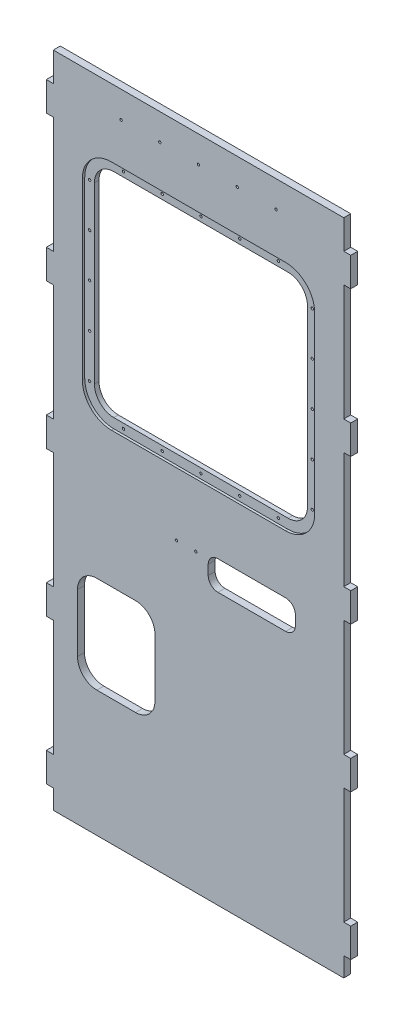
SolidWorks part; units mm, degrees
ref_plane "Front" through (0, 0, 0) normal (0, 0, 1) x (1, 0, 0)
ref_plane "Top" through (0, 0, 0) normal (0, 1, 0) x (1, 0, 0)
ref_plane "Right" through (0, 0, 0) normal (1, 0, 0) x (0, 0, -1)
sketch "Sketch2" plane through (0, 0, 0) normal (0, 0, 1) x (1, 0, 0)
  line L1 (0, 0) -> (381, 0)
  line L2 (0, 0) -> (0, 1727.2)
  line L3 (0, 1727.2) -> (381, 1727.2)
  line L4 (381, 0) -> (381, 1727.2)
  dimension "D1" = 381
  dimension "D2" = 1727.2
extrude "Boss-Extrude1" add sketch "Sketch2" against normal blind 18.288
sketch "Sketch3" plane through (0, 0, 0) normal (0, 0, 1) x (1, 0, 0)
  line L0 (0, 1727.2) -> (0, 0) construction
  line L1 (0, 50.8) -> (-18.288, 50.8)
  line L2 (0, 50.8) -> (0, 127)
  line L3 (0, 127) -> (-18.288, 127)
  line L4 (-18.288, 50.8) -> (-18.288, 127)
  dimension "D1" = 18.288
  dimension "D2" = 76.2
  dimension "D3" = 50.8
extrude "Boss-Extrude2" add sketch "Sketch3" against normal blind 18.288
pattern_linear "LPattern1" count 5 spacing 381 along (0, 1, 0) of "Boss-Extrude2"
mirror "Mirror1" about plane through (381, 0, -18.288) normal (1, 0, 0) of "Boss-Extrude1", "LPattern1", "Boss-Extrude2"
sketch "Sketch4" plane through (0, 0, 0) normal (0, 0, 1) x (1, 0, 0)
  line L0 (101.6, 1524) -> (660.4, 965.2) construction
  line L1 (152.4, 1524) -> (609.6, 1524)
  line L2 (101.6, 1473.2) -> (101.6, 1016)
  line L3 (152.4, 965.2) -> (609.6, 965.2)
  line L4 (660.4, 1473.2) -> (660.4, 1016)
  line L5 (660.4, 1524) -> (101.6, 965.2) construction
  line L7 (762, 1727.2) -> (0, 1727.2) construction
  line L96 (762, 1193.8) -> (762, 889) construction
  arc A0 (609.6, 965.2) -> (660.4, 1016) centre (609.6, 1016) ccw
  arc A1 (101.6, 1016) -> (152.4, 965.2) centre (152.4, 1016) ccw
  arc A2 (152.4, 1524) -> (101.6, 1473.2) centre (152.4, 1473.2) ccw
  arc A3 (609.6, 1524) -> (660.4, 1473.2) centre (609.6, 1473.2) cw
  point P6 (381, 1244.6)
  dimension "D5" = 50.8
  dimension "D1" = 558.8
  dimension "D2" = 558.8
  dimension "D4" = 482.6
  dimension "D6" = 381
extrude "Cut-Extrude2" cut sketch "Sketch4" against normal through all
sketch "Sketch5" plane through (0, 0, 0) normal (0, 0, 1) x (1, 0, 0)
  line L0 (101.6, 1524) -> (660.4, 965.2) construction
  line L1 (152.4, 1524) -> (609.6, 1524)
  line L2 (101.6, 1473.2) -> (101.6, 1016)
  line L3 (152.4, 965.2) -> (609.6, 965.2)
  line L4 (660.4, 1473.2) -> (660.4, 1016)
  line L5 (660.4, 1524) -> (101.6, 965.2) construction
  line L6 (762, 1727.2) -> (0, 1727.2) construction
  line L7 (381, 1727.2) -> (381, 0) construction
  line L8 (0, 0) -> (762, 0) construction
  line L96 (152.4, 1549.4) -> (609.6, 1549.4)
  line L97 (685.8, 1473.2) -> (685.8, 1016)
  line L98 (152.4, 939.8) -> (609.6, 939.8)
  line L99 (76.2, 1473.2) -> (76.2, 1016)
  arc A0 (609.6, 965.2) -> (660.4, 1016) centre (609.6, 1016) ccw
  arc A1 (101.6, 1016) -> (152.4, 965.2) centre (152.4, 1016) ccw
  arc A2 (152.4, 1524) -> (101.6, 1473.2) centre (152.4, 1473.2) ccw
  arc A3 (609.6, 1524) -> (660.4, 1473.2) centre (609.6, 1473.2) cw
  arc A4 (609.6, 1549.4) -> (685.8, 1473.2) centre (609.6, 1473.2) cw
  arc A5 (609.6, 939.8) -> (685.8, 1016) centre (609.6, 1016) ccw
  arc A6 (76.2, 1016) -> (152.4, 939.8) centre (152.4, 1016) ccw
  arc A7 (152.4, 1549.4) -> (76.2, 1473.2) centre (152.4, 1473.2) ccw
  point P34 (381, 1244.6)
  dimension "D5" = 50.8
  dimension "D2" = 558.8
  dimension "D3" = 25.4
  dimension "D4" = 177.8
  dimension "D6" = 609.6
extrude "Cut-Extrude4" cut sketch "Sketch5" against normal blind 6.35
sketch "Sketch6" plane through (0, 0, 0) normal (0, 0, 1) x (1, 0, 0)
  line L1 (266.7, 330.2) -> (63.5, 330.2)
  line L2 (266.7, 330.2) -> (266.7, 584.2)
  line L3 (266.7, 584.2) -> (63.5, 584.2)
  line L4 (63.5, 330.2) -> (63.5, 584.2)
  line L5 (266.7, 330.2) -> (63.5, 584.2) construction
  line L6 (266.7, 584.2) -> (63.5, 330.2) construction
  line L7 (0, 431.8) -> (0, 127) construction
  line L8 (0, 0) -> (762, 0) construction
  point P0 (165.1, 457.2)
  dimension "D1" = 203.2
  dimension "D2" = 254
  dimension "D3" = 330.2
  dimension "D4" = 63.5
extrude "Cut-Extrude5" cut sketch "Sketch6" against normal through all
sketch "Sketch7" plane through (0, 0, -6.35) normal (0, 0, 1) x (1, 0, 0)
  line L0 (381, 1727.2) -> (381, 0) construction
  line L1 (762, 1727.2) -> (0, 1727.2) construction
  line L2 (152.4, 939.8) -> (609.6, 939.8) construction
  line L3 (0, 0) -> (762, 0) construction
  line L4 (152.4, 965.2) -> (609.6, 965.2)
  line L5 (101.6, 1016) -> (101.6, 1473.2)
  line L6 (152.4, 1524) -> (609.6, 1524)
  line L7 (660.4, 1016) -> (660.4, 1473.2)
  circle A0 centre (381, 952.5) radius 3.175
  arc A1 (101.6, 1473.2) -> (152.4, 1524) centre (152.4, 1473.2) cw
  arc A2 (152.4, 965.2) -> (101.6, 1016) centre (152.4, 1016) cw
  arc A3 (609.6, 965.2) -> (660.4, 1016) centre (609.6, 1016) ccw
  arc A4 (609.6, 1524) -> (660.4, 1473.2) centre (609.6, 1473.2) cw
  circle A5 centre (482.6, 952.5) radius 3.175
  circle A6 centre (584.2, 952.5) radius 3.175
  circle A7 centre (177.8, 952.5) radius 3.175
  circle A8 centre (279.4, 952.5) radius 3.175
  circle A9 centre (584.2, 1536.7) radius 3.175
  circle A10 centre (482.6, 1536.7) radius 3.175
  circle A11 centre (381, 1536.7) radius 3.175
  circle A12 centre (279.4, 1536.7) radius 3.175
  circle A13 centre (177.8, 1536.7) radius 3.175
  circle A14 centre (673.1, 1244.8329) radius 3.175
  circle A15 centre (673.1, 1359.1329) radius 3.175
  circle A16 centre (673.1, 1473.4329) radius 3.175
  circle A17 centre (673.1, 1130.5329) radius 3.175
  circle A18 centre (673.1, 1016.2329) radius 3.175
  circle A19 centre (88.9, 1016.2329) radius 3.175
  circle A20 centre (88.9, 1130.5329) radius 3.175
  circle A21 centre (88.9, 1244.8329) radius 3.175
  circle A22 centre (88.9, 1359.1329) radius 3.175
  circle A23 centre (88.9, 1473.4329) radius 3.175
  point P10 (101.6, 1524)
  point P16 (660.4, 965.2)
  point P19 (660.4, 1524)
  point P30 (660.4, 1244.6)
  dimension "D1" = 12.7
  dimension "D2" = 558.8
  dimension "D5" = 50.8
  dimension "D6" = 50.8
  dimension "D8" = 12.7
  dimension "D3" = 0
  dimension "D4" = 558.8
  dimension "D9" = 3
  dimension "D11" = 279.4
  dimension "D7" = 3
  dimension "D10" = 3
extrude "Cut-Extrude6" cut sketch "Sketch7" against normal blind 25.4
fillet "Fillet1" radius 50.8 4 edges at (266.7, 330.2, -9.144) (63.5, 330.2, -9.144) (266.7, 584.2, -9.144) (63.5, 584.2, -9.144)
sketch "Sketch10" plane through (0, 0, 0) normal (0, 0, 1) x (1, 0, 0)
  line L0 (0, 0) -> (762, 0) construction
  line L1 (406.4, 787.4) -> (635, 787.4)
  line L2 (406.4, 787.4) -> (406.4, 711.2)
  line L3 (406.4, 711.2) -> (635, 711.2)
  line L4 (635, 787.4) -> (635, 711.2)
  line L5 (762, 812.8) -> (762, 508) construction
  dimension "D1" = 127
  dimension "D2" = 228.6
  dimension "D3" = 76.2
  dimension "D4" = 711.2
extrude "Cut-Extrude7" cut sketch "Sketch10" against normal blind 25.4
fillet "Fillet2" radius 25.4 4 edges at (635, 711.2, -9.144) (635, 787.4, -9.144) (406.4, 711.2, -9.144) (406.4, 787.4, -9.144)
sketch "Sketch12" plane through (0, 0, -18.288) normal (0, 0, -1) x (-1, 0, 0)
  circle A0 centre (-584.2, 1657.35) radius 3.175
  circle A1 centre (-482.6, 1657.35) radius 3.175
  circle A2 centre (-381, 1657.35) radius 3.175
  circle A3 centre (-279.4, 1657.35) radius 3.175
  circle A4 centre (-177.8, 1657.35) radius 3.175
  dimension "D1" = 5
extrude "Cut-Extrude10" cut sketch "Sketch12" against normal through all
sketch "Sketch13" plane through (0, 0, -18.288) normal (0, 0, -1) x (-1, 0, 0)
  circle A0 centre (-373.888, 774.7) radius 3.175
  circle A1 centre (-323.088, 774.7) radius 3.175
extrude "Cut-Extrude11" cut sketch "Sketch13" against normal through all
